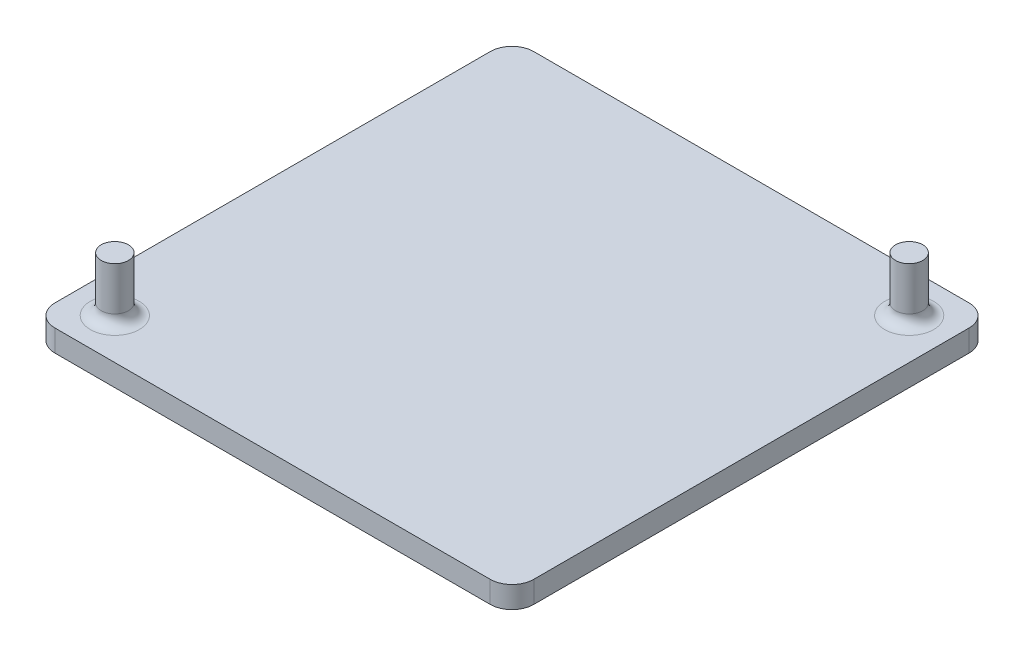
SolidWorks part; units mm, degrees
ref_plane "Front Plane" through (0, 0, 0) normal (0, 0, 1) x (1, 0, 0)
ref_plane "Top Plane" through (0, 0, 0) normal (0, 1, 0) x (1, 0, 0)
ref_plane "Right Plane" through (0, 0, 0) normal (1, 0, 0) x (0, 0, -1)
sketch "Sketch1" plane through (0, 0, 0) normal (0, 1, 0) x (1, 0, 0)
  line L1 (0, 0) -> (44, 0)
  line L2 (0, 0) -> (0, 44)
  line L3 (0, 44) -> (44, 44)
  line L4 (44, 0) -> (44, 44)
  dimension "D1" = 44
  dimension "D2" = 44
extrude "Boss-Extrude1" add sketch "Sketch1" along normal blind 2
sketch "Sketch2" plane through (0, 2, 0) normal (0, 1, 0) x (1, 0, 0)
  line L2 (0, 44) -> (0, 0) construction
  line L3 (0, 0) -> (44, 0) construction
  circle A0 centre (3.75, 3.75) radius 1.25
  circle A1 centre (40.25, 40.25) radius 1.25
  dimension "D5" = 2.5
  dimension "D1" = 3.75
  dimension "D2" = 3.75
  dimension "D3" = 36.5
  dimension "D4" = 36.5
extrude "Boss-Extrude4" add sketch "Sketch2" along normal blind 5
fillet "Fillet4" radius 2 4 edges at (44, 1, -44) (0, 1, -44) (0, 1, 0) (44, 1, 0)
fillet "Fillet5" radius 1 2 edges at (3.75, 2, -5) (40.25, 2, -41.5)
